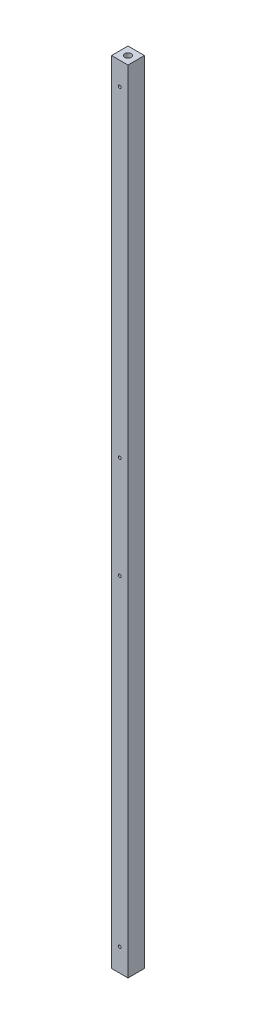
SolidWorks part; units mm, degrees
ref_plane "Front Plane" through (0, 0, 0) normal (0, 0, 1) x (1, 0, 0)
ref_plane "Top Plane" through (0, 0, 0) normal (0, 1, 0) x (1, 0, 0)
ref_plane "Right Plane" through (0, 0, 0) normal (1, 0, 0) x (0, 0, -1)
sketch "Sketch1" plane through (0, 0, 0) normal (0, 1, 0) x (1, 0, 0)
  line L1 (-6.35, 6.35) -> (6.35, 6.35)
  line L2 (-6.35, 6.35) -> (-6.35, -6.35)
  line L3 (-6.35, -6.35) -> (6.35, -6.35)
  line L4 (6.35, 6.35) -> (6.35, -6.35)
  line L5 (-6.35, 6.35) -> (6.35, -6.35) construction
  line L6 (-6.35, -6.35) -> (6.35, 6.35) construction
  point P0 (0, 0)
extrude "Boss-Extrude1" add sketch "Sketch1" along normal blind 609.6
hole_wizard "1/4-20 Tapped Hole1" positions "3DSketch6" profile "Sketch8" tap size "1/4-20" standard "ANSI Inch"
sketch3d "3DSketch6"
  point P0 (0, 0, 0)
sketch "Sketch8" plane through (0, 0, 0) normal (1, 0, 0) x (0, 0, -1)
  line L0 (0, 0) -> (0, 14.2338)
  line L1 (0, 14.2338) -> (2.5527, 12.7)
  line L2 (2.5527, 12.7) -> (2.5527, 0)
  line L5 (2.5527, 0) -> (0, 0)
  line L10 (0, 14.2338) -> (-2.5527, 12.7) construction
  line L11 (0, -6.35) -> (0, 107.95) construction
  dimension "Tap Drill Dia." = 5.1054
  dimension "Tap Drill Depth" = 12.7
  dimension "Drill Angle" = 118
cosmetic thread "Hole Thread3" parameters "D1"=11.43, "D2"=6.35
hole_wizard "#4-40 Tapped Hole2" positions "3DSketch9" profile "Sketch13" tap size "#4-40" standard "ANSI Inch" end condition through all
sketch3d "3DSketch9"
  point P0 (0, 17.7527, 6.35)
  point P2 (0, 265.4027, 6.35)
sketch "Sketch13" plane through (0, 17.7527, 6.35) normal (1, 0, 0) x (0, -1, 0)
  line L0 (0, 0) -> (0, 12.7)
  line L1 (0, 12.7) -> (1.1303, 12.7)
  line L2 (1.1303, 12.7) -> (1.1303, 0)
  line L5 (1.1303, 0) -> (0, 0)
  line L11 (0, -6.35) -> (0, 107.95) construction
  dimension "Thru Tap Drill Dia." = 2.2606
  dimension "Thru Tap Drill Depth" = 12.7
cosmetic thread "Hole Thread13" parameters "D2"=2.8448
cosmetic thread "Hole Thread14" parameters "D2"=2.8448
ref_plane "Plane1" through (0, 304.8, 0) normal (0, 1, 0) x (1, 0, 0)
mirror "Mirror1" about plane through (0, 304.8, 0) normal (0, 1, 0) of "#4-40 Tapped Hole2", "1/4-20 Tapped Hole1"
